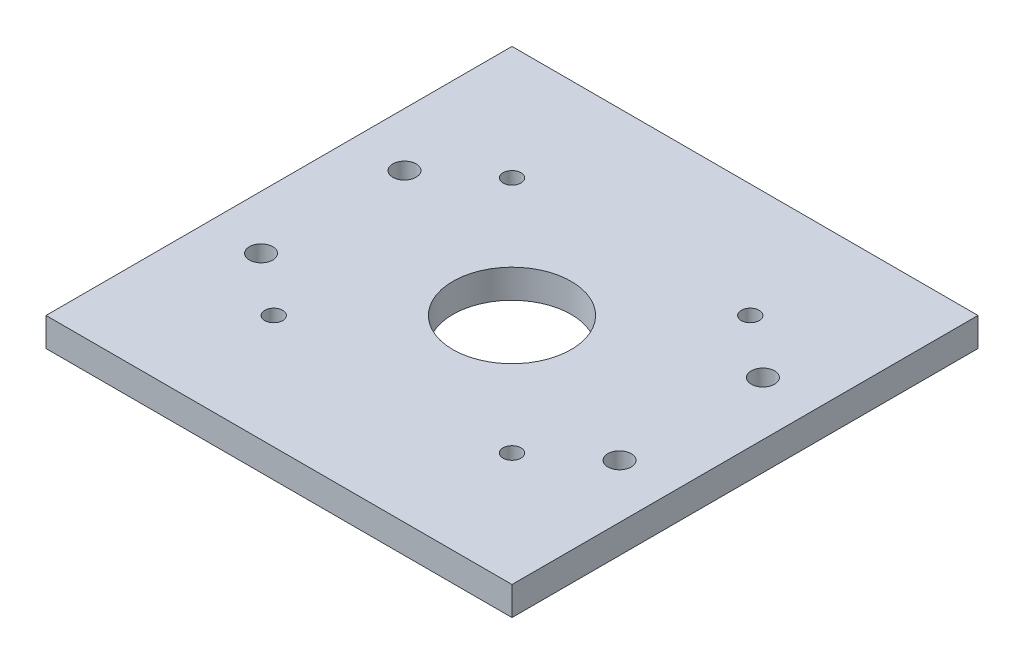
SolidWorks part; units mm, degrees
ref_plane "Front Plane" through (0, 0, 0) normal (0, 0, 1) x (1, 0, 0)
ref_plane "Top Plane" through (0, 0, 0) normal (0, 1, 0) x (1, 0, 0)
ref_plane "Right Plane" through (0, 0, 0) normal (1, 0, 0) x (0, 0, -1)
sketch "Sketch1" plane through (0, 0, 0) normal (0, 1, 0) x (1, 0, 0)
  line L0 (-333.4703, -142.4091) -> (-203.4703, -142.4091) construction
  line L1 (-333.4703, -207.4091) -> (-203.4703, -207.4091)
  line L2 (-333.4703, -207.4091) -> (-333.4703, -77.4091)
  line L3 (-333.4703, -77.4091) -> (-203.4703, -77.4091)
  line L4 (-203.4703, -207.4091) -> (-203.4703, -77.4091)
  line L5 (-268.4703, -207.4091) -> (-268.4703, -77.4091) construction
  circle A0 centre (-268.4703, -142.4091) radius 16.5
  dimension "D2" = 33
  dimension "D1" = 130
extrude "Boss-Extrude1" add sketch "Sketch1" along normal blind 8
sketch "Sketch2" plane through (0, 8, 0) normal (0, 1, 0) x (1, 0, 0)
  line L1 (-333.4703, -77.4091) -> (-333.4703, -207.4091) construction
  line L3 (-333.4703, -207.4091) -> (-203.4703, -207.4091) construction
  circle A0 centre (-318.4703, -162.4091) radius 3.25
  circle A1 centre (-318.4703, -122.4091) radius 3.25
  circle A2 centre (-218.4703, -122.4091) radius 3.25
  circle A3 centre (-218.4703, -162.4091) radius 3.25
  dimension "D1" = 6.5
  dimension "D2" = 115
  dimension "D3" = 15
  dimension "D4" = 15
  dimension "D5" = 115
  dimension "D6" = 85
  dimension "D7" = 85
  dimension "D8" = 45
  dimension "D9" = 45
extrude "Cut-Extrude1" cut sketch "Sketch2" against normal through all
hole_wizard "M6x1.0 Tapped Hole2" positions "Sketch4" profile "Sketch5" tap size "M6x1.0" standard "ANSI Metric" end condition through all
sketch "Sketch4" plane through (0, 8, 0) normal (0, 1, 0) x (1, 0, 0)
  line L0 (-333.4703, -77.4091) -> (-333.4703, -207.4091) construction
  line L1 (-333.4703, -207.4091) -> (-203.4703, -207.4091) construction
  point P0 (-301.7043, -109.1751)
  point P2 (-235.2363, -109.1751)
  point P4 (-235.2363, -175.6431)
  point P6 (-301.7043, -175.6431)
  dimension "D1" = 31.766
  dimension "D2" = 98.234
  dimension "D3" = 31.766
  dimension "D4" = 31.766
  dimension "D5" = 31.766
  dimension "D6" = 98.234
  dimension "D7" = 98.234
  dimension "D8" = 98.234
sketch "Sketch5" plane through (-301.7043, 8, 109.1751) normal (1, 0, 0) x (0, 0, 1)
  line L0 (0, 0) -> (0, 8)
  line L1 (0, 8) -> (2.5, 8)
  line L2 (2.5, 8) -> (2.5, 0)
  line L5 (2.5, 0) -> (0, 0)
  line L11 (0, -6.35) -> (0, 107.95) construction
  dimension "Thru Tap Drill Dia." = 5
  dimension "Thru Tap Drill Depth" = 8
cosmetic thread "Hole Thread1" parameters "D2"=6
cosmetic thread "Hole Thread2" parameters "D2"=6
cosmetic thread "Hole Thread3" parameters "D2"=6
cosmetic thread "Hole Thread4" parameters "D2"=6
